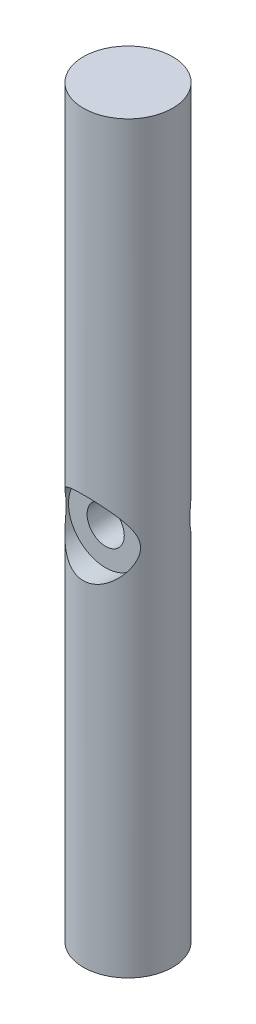
SolidWorks part; units mm, degrees
ref_plane "Front Plane" through (0, 0, 0) normal (0, 0, 1) x (1, 0, 0)
ref_plane "Top Plane" through (0, 0, 0) normal (0, 1, 0) x (1, 0, 0)
ref_plane "Right Plane" through (0, 0, 0) normal (1, 0, 0) x (0, 0, -1)
sketch "Sketch1" plane through (0, 0, 0) normal (0, 1, 0) x (1, 0, 0)
  line L1 (0, 0) -> (12, 0)
  line L2 (0, 0) -> (0, -12)
  line L3 (0, -12) -> (12, -12)
  line L4 (12, 0) -> (12, -12)
  dimension "D1" = 12
  dimension "D2" = 12
extrude "Boss-Extrude1" add sketch "Sketch1" along normal blind 100
sketch "Sketch4" plane through (0, 100, 0) normal (0, 1, 0) x (1, 0, 0)
  line L1 (12, 0) -> (0, 0) construction
  line L2 (6, 0) -> (6, -12)
  line L3 (0, -12) -> (12, -12) construction
  circle A0 centre (6, -6) radius 6
  dimension "D1" = 12
sketch "Sketch5" plane through (0, 0, 12) normal (0, 0, 1) x (1, 0, 0)
  line L0 (6, 0) -> (6, 50)
  line L1 (0, 0) -> (12, 0) construction
  circle A0 centre (6, 50) radius 2.5
  circle A1 centre (6, 50) radius 5
  dimension "D2" = 5
  dimension "D3" = 10
  dimension "D1" = 50
extrude "Cut-Extrude1" cut sketch "Sketch5" against normal up to next
sketch "Sketch6" plane through (0, 0, 12) normal (0, 0, 1) x (1, 0, 0)
  circle A0 centre (6, 50) radius 5
  circle A1 centre (6, 50) radius 2.5
  dimension "D1" = 10
extrude "Cut-Extrude3" cut sketch "Sketch6" against normal blind 3 contours A0
sketch "Sketch7" plane through (0, 0, 0) normal (0, 0, -1) x (-1, 0, 0)
  circle A0 centre (-6, 50) radius 5
  circle A1 centre (-6, 50) radius 2.5
  dimension "D1" = 10
extrude "Cut-Extrude4" cut sketch "Sketch7" against normal blind 3
sketch "Sketch8" plane through (0, 100, 0) normal (0, 1, 0) x (1, 0, 0)
  circle A0 centre (6, -6) radius 6
  circle A1 centre (6, -6) radius 6
  circle A2 centre (6, -6) radius 6
  circle A3 centre (6, -6) radius 6
  point P7 (0, 0)
  line M2 (0, 0) -> (0, -12)
  line M3 (0, -12) -> (12, -12)
  line M4 (12, -12) -> (12, 0)
  line M5 (12, 0) -> (0, 0)
extrude "Cut-Extrude5" cut sketch "Sketch8" against normal blind 100 contours A0 M2 M3 | A0 M3 M4 | A0 M4 M5 | A0 M5 M2
